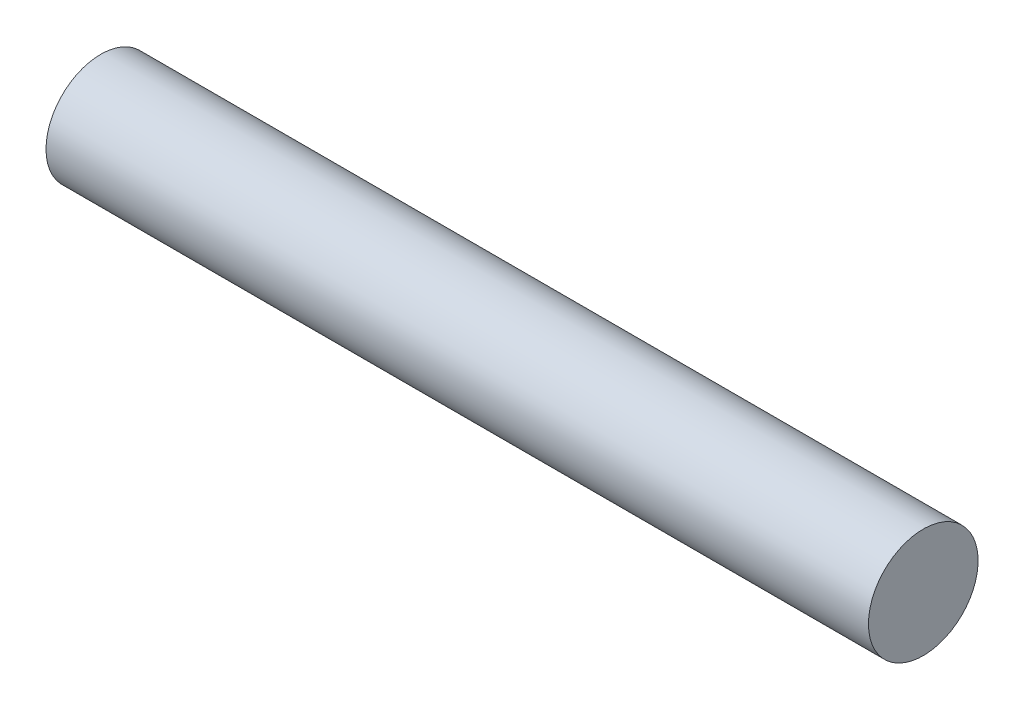
SolidWorks part; units mm, degrees
material "1345 合金"
ref_plane "前视" through (0, 0, 0) normal (0, 0, 1) x (1, 0, 0)
ref_plane "上视" through (0, 0, 0) normal (0, 1, 0) x (1, 0, 0)
ref_plane "右视" through (0, 0, 0) normal (1, 0, 0) x (0, 0, -1)
sketch "草图1" plane through (0, 0, 0) normal (0, 0, 1) x (1, 0, 0)
  line L0 (-32.6697, 0) -> (12.3303, 0)
  line L1 (12.3303, 0) -> (12.3303, 3)
  line L2 (12.3303, 3) -> (-32.6697, 3)
  line L3 (-32.6697, 3) -> (-32.6697, 0)
  dimension "D1" = 3
  dimension "D2" = 45
revolve "旋转1" add sketch "草图1" angle 360 about L0
